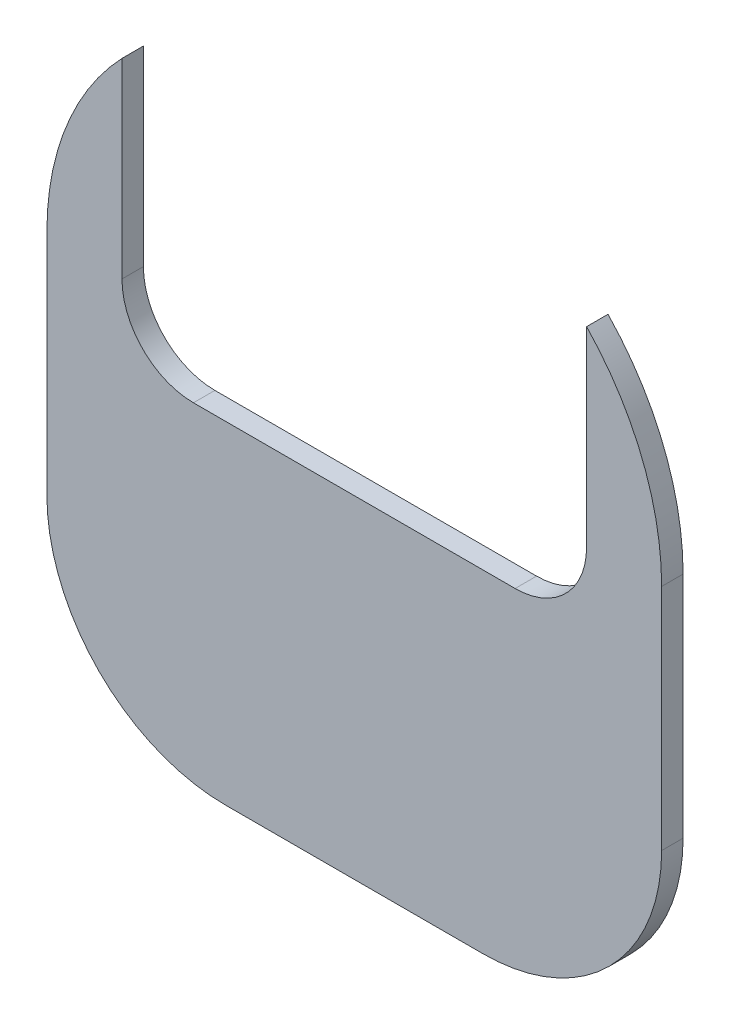
SolidWorks part; units mm, degrees
ref_plane "Front Plane" through (0, 0, 0) normal (0, 0, 1) x (1, 0, 0)
ref_plane "Top Plane" through (0, 0, 0) normal (0, 1, 0) x (1, 0, 0)
ref_plane "Right Plane" through (0, 0, 0) normal (1, 0, 0) x (0, 0, -1)
sketch "Sketch1" plane through (0, 0, 0) normal (0, 0, 1) x (1, 0, 0)
  line L0 (0, 8.5) -> (0, -86.5) construction
  line L1 (-43, 8.5) -> (43, 8.5) construction
  line L2 (-43, 8.5) -> (-43, -86.5) construction
  line L3 (-43, -86.5) -> (43, -86.5) construction
  line L4 (43, 8.5) -> (43, -86.5) construction
  line L5 (-5, 8.5) -> (5, 8.5)
  line L6 (-18, -86.5) -> (18, -86.5) construction
  line L7 (-43, -29.5) -> (43, -29.5) construction
  line L8 (-43, -29.5) -> (-43, -61.5)
  line L9 (-43, -61.5) -> (43, -61.5) construction
  line L10 (43, -29.5) -> (43, -61.5)
  line L11 (-0.5, -86.5) -> (0.5, -86.5) construction
  line L12 (-18, -86.5) -> (-0.5, -86.5)
  line L13 (0.5, -86.5) -> (18, -86.5)
  line L14 (-0.5, -86.5) -> (0.5, -86.5)
  line L15 (55, 0) -> (-55, 0) construction
  arc A0 (-43, -29.5) -> (-5, 8.5) centre (-5, -29.5) cw
  arc A1 (5, 8.5) -> (43, -29.5) centre (5, -29.5) cw
  arc A2 (-43, -61.5) -> (-18, -86.5) centre (-18, -61.5) ccw
  arc A3 (18, -86.5) -> (43, -61.5) centre (18, -61.5) ccw
  point P10 (0, 8.5)
  point P19 (0, -86.5)
  point P23 (0, -86.5)
  dimension "D3" = 25
  dimension "D4" = 38
  dimension "D1" = 95
  dimension "D2" = 86
  dimension "D5" = 1
  dimension "D6" = 8.5
extrude "Boss-Extrude1" add sketch "Sketch1" along normal blind 3
sketch "Sketch2" plane through (0, 0, 3) normal (0, 0, 1) x (1, 0, 0)
  line L0 (0, -1.65) -> (0, 1.65) construction
  line L1 (-22.5, -40) -> (22.5, -40)
  line L2 (-32.5, -30) -> (-32.5, 20)
  line L3 (-22.5, 30) -> (22.5, 30)
  line L4 (32.5, -30) -> (32.5, 20)
  line L5 (-32.5, -40) -> (32.5, 30) construction
  line L6 (-32.5, 30) -> (32.5, -40) construction
  line L7 (1.65, 0) -> (-1.65, 0) construction
  arc A0 (22.5, 30) -> (32.5, 20) centre (22.5, 20) cw
  arc A1 (22.5, -40) -> (32.5, -30) centre (22.5, -30) ccw
  arc A2 (-22.5, -40) -> (-32.5, -30) centre (-22.5, -30) cw
  arc A3 (-32.5, 20) -> (-22.5, 30) centre (-22.5, 20) cw
  point P0 (0, -5)
  dimension "D4" = 10
  dimension "D1" = 65
  dimension "D2" = 70
  dimension "D3" = 40
extrude "Cut-Extrude1" cut sketch "Sketch2" against normal blind 10
